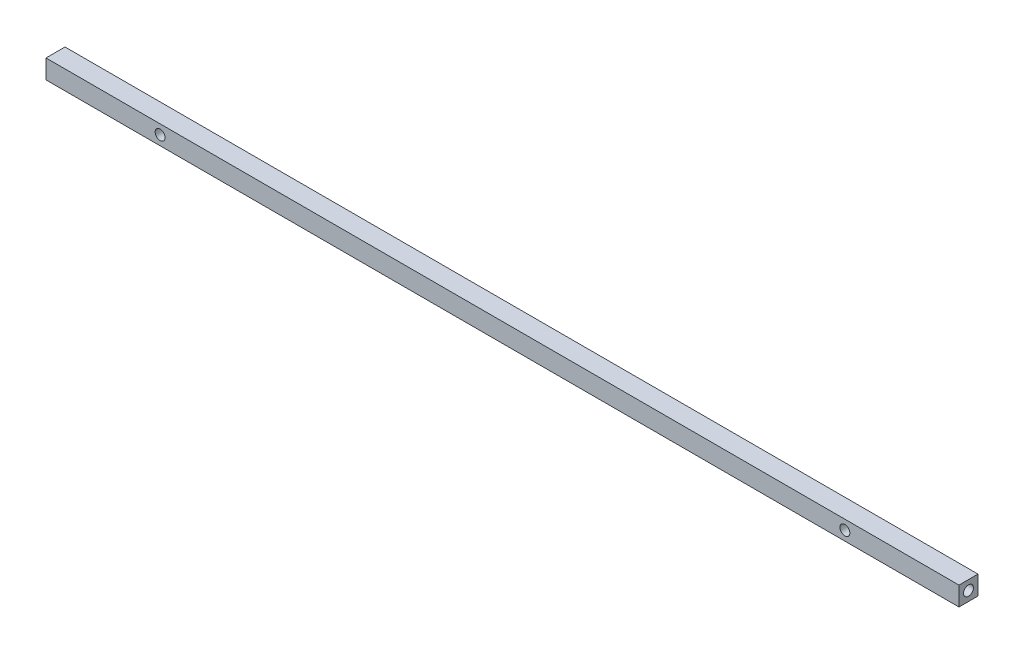
SolidWorks part; units mm, degrees
ref_plane "Front Plane" through (0, 0, 0) normal (0, 0, 1) x (1, 0, 0)
ref_plane "Top Plane" through (0, 0, 0) normal (0, 1, 0) x (1, 0, 0)
ref_plane "Right Plane" through (0, 0, 0) normal (1, 0, 0) x (0, 0, -1)
sketch "Sketch1" plane through (0, 0, 0) normal (1, 0, 0) x (0, 0, -1)
  line L5 (-3.175, -3.175) -> (3.175, -3.175)
  line L6 (-3.175, -3.175) -> (-3.175, 3.175)
  line L7 (-3.175, 3.175) -> (3.175, 3.175)
  line L8 (3.175, -3.175) -> (3.175, 3.175)
  line L9 (-3.175, -3.175) -> (3.175, 3.175) construction
  line L10 (-3.175, 3.175) -> (3.175, -3.175) construction
  point P0 (0, 0)
  dimension "D1" = 6.35
extrude "Boss-Extrude1" add sketch "Sketch1" along normal mid plane 304.8
sketch "Sketch4" plane through (152.4, 0, 0) normal (1, 0, 0) x (0, 0, -1)
  circle A0 centre (0, 0) radius 1.651
  dimension "D1" = 3.302
extrude "Cut-Extrude1" cut sketch "Sketch4" against normal blind 12.7
sketch "Sketch5" plane through (0, 0, 3.175) normal (0, 0, 1) x (1, 0, 0)
  circle A0 centre (114.3, 0) radius 1.651
  circle A1 centre (114.3, 0) radius 1.651 construction
  point P2 (0, 0)
  dimension "D1" = 3.302
extrude "Cut-Extrude2" cut sketch "Sketch5" against normal through all
mirror "Mirror1" about plane through (0, 0, 0) normal (1, 0, 0) of "Cut-Extrude1", "Cut-Extrude2"
